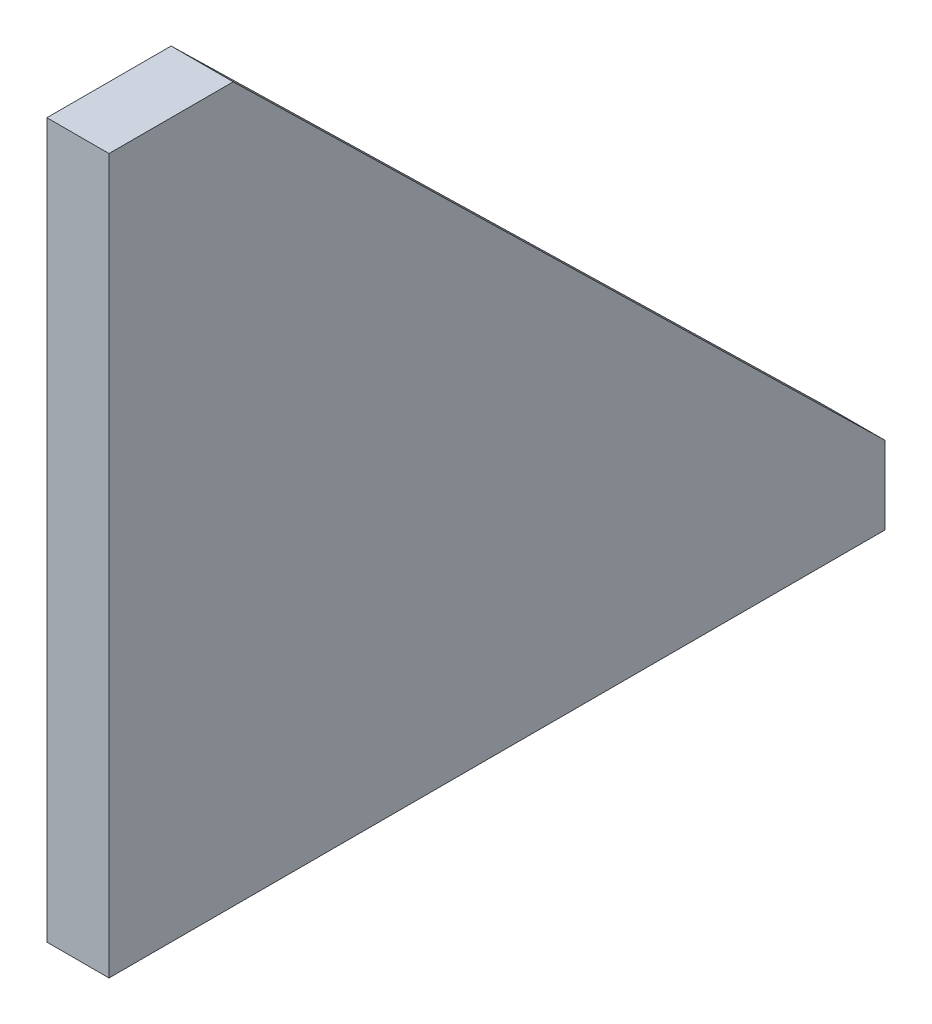
SolidWorks part; units mm, degrees
ref_plane "Front Plane" through (0, 0, 0) normal (0, 0, 1) x (1, 0, 0)
ref_plane "Top Plane" through (0, 0, 0) normal (0, 1, 0) x (1, 0, 0)
ref_plane "Right Plane" through (0, 0, 0) normal (1, 0, 0) x (0, 0, -1)
sketch "Sketch1" plane through (0, 0, 0) normal (1, 0, 0) x (0, 0, -1)
  line L0 (-85, 115) -> (125, -90)
  line L1 (-125, -115) -> (125, -115)
  line L2 (-125, -115) -> (-125, 115)
  line L3 (-125, 115) -> (-85, 115)
  line L4 (125, -115) -> (125, -90)
  line L5 (-125, -115) -> (125, 115) construction
  line L6 (-125, 115) -> (125, -115) construction
  point P0 (0, 0)
  dimension "D1" = 94.772
  dimension "D3" = 25
  dimension "D4" = 40
  dimension "D5" = 230
  dimension "D6" = 250
extrude "Boss-Extrude1" add sketch "Sketch1" along normal blind 20
